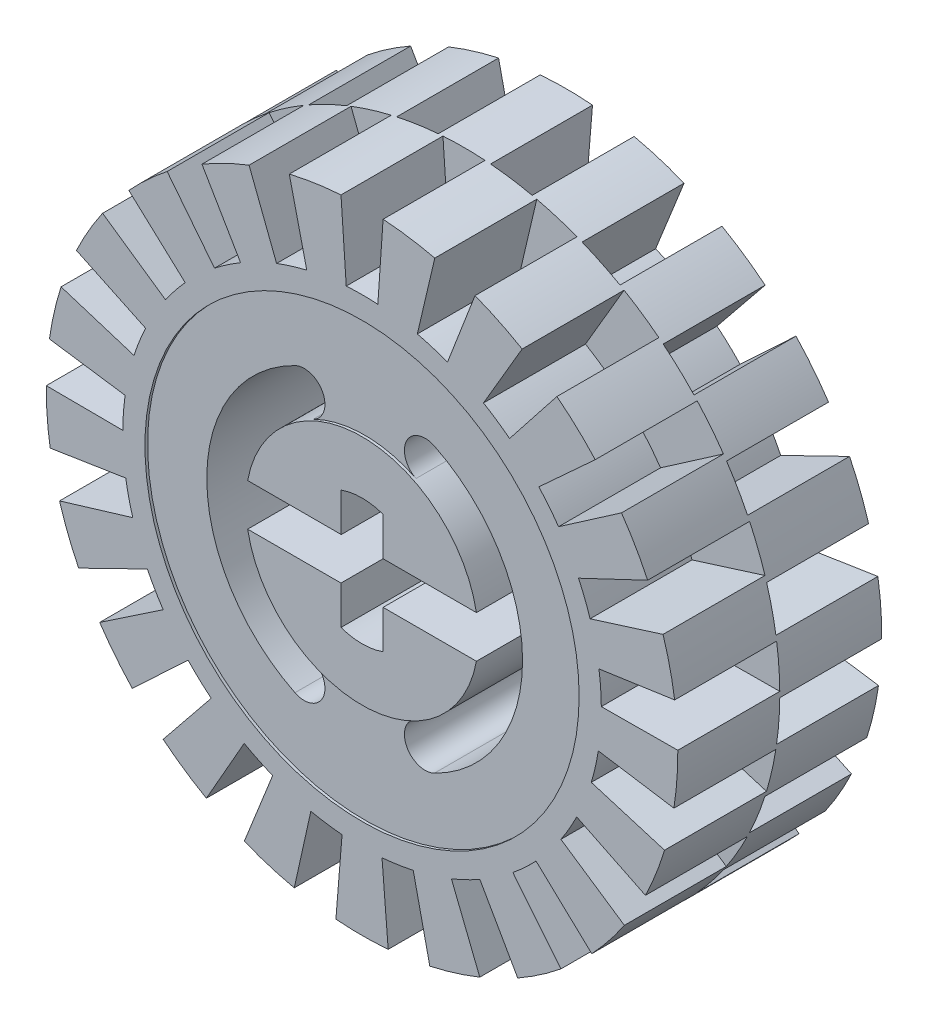
SolidWorks part; units mm, degrees
ref_plane "Plan de face" through (0, 0, 0) normal (0, 0, 1) x (1, 0, 0)
ref_plane "Plan de dessus" through (0, 0, 0) normal (0, 1, 0) x (1, 0, 0)
ref_plane "Plan de droite" through (0, 0, 0) normal (1, 0, 0) x (0, 0, -1)
sketch "Esquisse1" plane through (0, 0, 0) normal (0, 0, 1) x (1, 0, 0)
  circle A0 centre (0, 0) radius 12
  dimension "D1" = 24
extrude "Boss.-Extru.1" add sketch "Esquisse1" along normal blind 7.75
sketch "Esquisse2" plane through (0, 0, 7.75) normal (0, 0, 1) x (1, 0, 0)
  line L0 (-0.8, 11.9733) -> (-0.6, 9.0733) construction
  line L1 (-0.6, 9.0733) -> (0.6, 9.0733) construction
  line L2 (0.8, 11.9733) -> (0.6, 9.0733) construction
  line L3 (-0.8, 11.9733) -> (-0.6, 9.0733)
  line L4 (-0.8, 11.9733) -> (0.8, 11.9733) construction
  line L5 (0, 11.9733) -> (0, 0) construction
  line L6 (0.6, 9.0733) -> (0.8, 11.9733)
  line L7 (-0.8, 11.9733) -> (-1.2164, 18.0106)
  line L8 (-1.2164, 18.0106) -> (1.2164, 18.0106)
  line L9 (1.2164, 18.0106) -> (0.8, 11.9733)
  line L10 (2.7647, 11.6772) -> (2.1011, 8.8471)
  line L11 (2.7647, 11.6772) -> (4.1464, 17.5689)
  line L12 (4.1464, 17.5689) -> (6.471, 16.8519)
  line L13 (6.471, 16.8519) -> (4.2937, 11.2056)
  line L14 (3.2477, 8.4933) -> (4.2937, 11.2056)
  line L15 (6.0838, 10.3435) -> (4.6154, 7.8347)
  line L16 (6.0838, 10.3435) -> (9.1407, 15.5662)
  line L17 (9.1407, 15.5662) -> (11.1507, 14.1958)
  line L18 (11.1507, 14.1958) -> (7.4058, 9.4422)
  line L19 (5.6069, 7.1587) -> (7.4058, 9.4422)
  line L20 (8.8623, 8.0907) -> (6.7197, 6.1262)
  line L21 (8.8623, 8.0907) -> (13.3228, 12.1804)
  line L22 (13.3228, 12.1804) -> (14.8396, 10.2784)
  line L23 (14.8396, 10.2784) -> (9.8599, 6.8398)
  line L24 (7.4679, 5.188) -> (9.8599, 6.8398)
  line L25 (10.8534, 5.119) -> (8.2269, 3.8734)
  line L26 (10.8534, 5.119) -> (16.3212, 7.7123)
  line L27 (16.3212, 7.7123) -> (17.21, 5.4477)
  line L28 (17.21, 5.4477) -> (11.4379, 3.6296)
  line L29 (8.6653, 2.7563) -> (11.4379, 3.6296)
  line L30 (11.88, 1.6925) -> (9.0031, 1.2764)
  line L31 (11.88, 1.6925) -> (17.8693, 2.5589)
  line L32 (17.8693, 2.5589) -> (18.0511, 0.133)
  line L33 (18.0511, 0.133) -> (11.9996, 0.097)
  line L34 (9.0928, 0.0797) -> (11.9996, 0.097)
  line L35 (11.8511, -1.8844) -> (8.9793, -1.434)
  line L36 (11.8511, -1.8844) -> (17.8297, -2.8219)
  line L37 (17.8297, -2.8219) -> (17.2883, -5.1936)
  line L38 (17.2883, -5.1936) -> (11.4951, -3.4443)
  line L39 (8.7123, -2.604) -> (11.4951, -3.4443)
  line L40 (10.7692, -5.2938) -> (8.1577, -4.017)
  line L41 (10.7692, -5.2938) -> (16.2058, -7.9519)
  line L42 (16.2058, -7.9519) -> (14.9894, -10.0587)
  line L43 (14.9894, -10.0587) -> (9.9692, -6.6795)
  line L44 (7.5577, -5.0563) -> (9.9692, -6.6795)
  line L45 (8.7304, -8.2329) -> (6.6112, -6.2431)
  line L46 (8.7304, -8.2329) -> (13.142, -12.3753)
  line L47 (13.142, -12.3753) -> (11.3586, -14.03)
  line L48 (11.3586, -14.03) -> (7.5575, -9.3212)
  line L49 (5.7316, -7.0593) -> (7.5575, -9.3212)
  line L50 (5.9158, -10.4405) -> (4.4773, -7.9144)
  line L51 (5.9158, -10.4405) -> (8.9104, -15.6992)
  line L52 (8.9104, -15.6992) -> (6.7186, -16.7547)
  line L53 (6.7186, -16.7547) -> (4.4742, -11.1347)
  line L54 (3.3962, -8.4351) -> (4.4742, -11.1347)
  line L55 (2.5756, -11.7203) -> (1.9456, -8.8825)
  line L56 (2.5756, -11.7203) -> (3.8871, -17.6281)
  line L57 (3.8871, -17.6281) -> (1.4816, -17.9907)
  line L58 (1.4816, -17.9907) -> (0.9935, -11.9588)
  line L59 (0.759, -9.0614) -> (0.9935, -11.9588)
  line L60 (-0.9935, -11.9588) -> (-0.759, -9.0614)
  line L61 (-0.9935, -11.9588) -> (-1.4816, -17.9907)
  line L62 (-1.4816, -17.9907) -> (-3.8871, -17.6281)
  line L63 (-3.8871, -17.6281) -> (-2.5756, -11.7203)
  line L64 (-1.9456, -8.8825) -> (-2.5756, -11.7203)
  line L65 (-4.4742, -11.1347) -> (-3.3962, -8.4351)
  line L66 (-4.4742, -11.1347) -> (-6.7186, -16.7547)
  line L67 (-6.7186, -16.7547) -> (-8.9104, -15.6992)
  line L68 (-8.9104, -15.6992) -> (-5.9158, -10.4405)
  line L69 (-4.4773, -7.9144) -> (-5.9158, -10.4405)
  line L70 (-7.5575, -9.3212) -> (-5.7316, -7.0593)
  line L71 (-7.5575, -9.3212) -> (-11.3586, -14.03)
  line L72 (-11.3586, -14.03) -> (-13.142, -12.3753)
  line L73 (-13.142, -12.3753) -> (-8.7304, -8.2329)
  line L74 (-6.6112, -6.2431) -> (-8.7304, -8.2329)
  line L75 (-9.9692, -6.6795) -> (-7.5577, -5.0563)
  line L76 (-9.9692, -6.6795) -> (-14.9894, -10.0587)
  line L77 (-14.9894, -10.0587) -> (-16.2058, -7.9519)
  line L78 (-16.2058, -7.9519) -> (-10.7692, -5.2938)
  line L79 (-8.1577, -4.017) -> (-10.7692, -5.2938)
  line L80 (-11.4951, -3.4443) -> (-8.7123, -2.604)
  line L81 (-11.4951, -3.4443) -> (-17.2883, -5.1936)
  line L82 (-17.2883, -5.1936) -> (-17.8297, -2.8219)
  line L83 (-17.8297, -2.8219) -> (-11.8511, -1.8844)
  line L84 (-8.9793, -1.434) -> (-11.8511, -1.8844)
  line L85 (-11.9996, 0.097) -> (-9.0928, 0.0797)
  line L86 (-11.9996, 0.097) -> (-18.0511, 0.133)
  line L87 (-18.0511, 0.133) -> (-17.8693, 2.5589)
  line L88 (-17.8693, 2.5589) -> (-11.88, 1.6925)
  line L89 (-9.0031, 1.2764) -> (-11.88, 1.6925)
  line L90 (-11.4379, 3.6296) -> (-8.6653, 2.7563)
  line L91 (-11.4379, 3.6296) -> (-17.21, 5.4477)
  line L92 (-17.21, 5.4477) -> (-16.3212, 7.7123)
  line L93 (-16.3212, 7.7123) -> (-10.8534, 5.119)
  line L94 (-8.2269, 3.8734) -> (-10.8534, 5.119)
  line L95 (-9.8599, 6.8398) -> (-7.4679, 5.188)
  line L96 (-9.8599, 6.8398) -> (-14.8396, 10.2784)
  line L97 (-14.8396, 10.2784) -> (-13.3228, 12.1804)
  line L98 (-13.3228, 12.1804) -> (-8.8623, 8.0907)
  line L99 (-6.7197, 6.1262) -> (-8.8623, 8.0907)
  line L100 (-7.4058, 9.4422) -> (-5.6069, 7.1587)
  line L101 (-7.4058, 9.4422) -> (-11.1507, 14.1958)
  line L102 (-11.1507, 14.1958) -> (-9.1407, 15.5662)
  line L103 (-9.1407, 15.5662) -> (-6.0838, 10.3435)
  line L104 (-4.6154, 7.8347) -> (-6.0838, 10.3435)
  line L105 (-4.2937, 11.2056) -> (-3.2477, 8.4933)
  line L106 (-4.2937, 11.2056) -> (-6.471, 16.8519)
  line L107 (-6.471, 16.8519) -> (-4.1464, 17.5689)
  line L108 (-4.1464, 17.5689) -> (-2.7647, 11.6772)
  line L109 (-2.1011, 8.8471) -> (-2.7647, 11.6772)
  circle A1 centre (0, 0) radius 12 construction
  arc A2 (0.6, 9.0733) -> (-0.6, 9.0733) centre (0, 0) ccw
  arc A3 (3.2477, 8.4933) -> (2.1011, 8.8471) centre (0, 0) ccw
  arc A4 (5.6069, 7.1587) -> (4.6154, 7.8347) centre (0, 0) ccw
  arc A5 (7.4679, 5.188) -> (6.7197, 6.1262) centre (0, 0) ccw
  arc A6 (8.6653, 2.7563) -> (8.2269, 3.8734) centre (0, 0) ccw
  arc A7 (9.0928, 0.0797) -> (9.0031, 1.2764) centre (0, 0) ccw
  arc A8 (8.7123, -2.604) -> (8.9793, -1.434) centre (0, 0) ccw
  arc A9 (7.5577, -5.0563) -> (8.1577, -4.017) centre (0, 0) ccw
  arc A10 (5.7316, -7.0593) -> (6.6112, -6.2431) centre (0, 0) ccw
  arc A11 (3.3962, -8.4351) -> (4.4773, -7.9144) centre (0, 0) ccw
  arc A12 (0.759, -9.0614) -> (1.9456, -8.8825) centre (0, 0) ccw
  arc A13 (-1.9456, -8.8825) -> (-0.759, -9.0614) centre (0, 0) ccw
  arc A14 (-4.4773, -7.9144) -> (-3.3962, -8.4351) centre (0, 0) ccw
  arc A15 (-6.6112, -6.2431) -> (-5.7316, -7.0593) centre (0, 0) ccw
  arc A16 (-8.1577, -4.017) -> (-7.5577, -5.0563) centre (0, 0) ccw
  arc A17 (-8.9793, -1.434) -> (-8.7123, -2.604) centre (0, 0) ccw
  arc A18 (-9.0031, 1.2764) -> (-9.0928, 0.0797) centre (0, 0) ccw
  arc A19 (-8.2269, 3.8734) -> (-8.6653, 2.7563) centre (0, 0) ccw
  arc A20 (-6.7197, 6.1262) -> (-7.4679, 5.188) centre (0, 0) ccw
  arc A21 (-4.6154, 7.8347) -> (-5.6069, 7.1587) centre (0, 0) ccw
  arc A22 (-2.1011, 8.8471) -> (-3.2477, 8.4933) centre (0, 0) ccw
  point P1 (0, 9.0733)
  point P134 (0, 0)
  dimension "D1" = 2.9
  dimension "D2" = 1.2
  dimension "D3" = 21
  dimension "D4" = 1.6
extrude "Enlèv. mat.-Extru.1" cut sketch "Esquisse2" against normal blind 3.875
sketch "Esquisse3" plane through (0, 0, 0) normal (0, 0, -1) x (-1, 0, 0)
  line L0 (0, 0) -> (2.0891, 13.9787) construction
  line L1 (0.9786, 11.96) -> (2.561, 11.7235) construction
  line L2 (1.1507, 14.119) -> (0.7474, 9.06)
  line L3 (1.1507, 14.119) -> (3.0276, 13.8385)
  line L4 (3.0276, 13.8385) -> (1.9342, 8.8827)
  line L5 (0, 0) -> (17.443, 0) construction
  line L6 (5.2612, 13.1526) -> (3.3847, 8.4372)
  line L7 (5.2612, 13.1526) -> (6.9721, 12.3313)
  line L8 (6.9721, 12.3313) -> (4.4665, 7.9179)
  line L9 (8.9042, 11.0175) -> (5.7212, 7.0647)
  line L10 (8.9042, 11.0175) -> (10.297, 9.7284)
  line L11 (10.297, 9.7284) -> (6.6019, 6.2496)
  line L12 (11.7561, 7.9034) -> (7.5494, 5.0645)
  line L13 (11.7561, 7.9034) -> (12.7071, 6.2611)
  line L14 (12.7071, 6.2611) -> (8.1507, 4.026)
  line L15 (13.5634, 4.0871) -> (8.7068, 2.6143)
  line L16 (13.5634, 4.0871) -> (13.988, 2.2374)
  line L17 (13.988, 2.2374) -> (8.9753, 1.4447)
  line L18 (14.1655, -0.0923) -> (9.0906, -0.0682)
  line L19 (14.1655, -0.0923) -> (14.0261, -1.985)
  line L20 (14.0261, -1.985) -> (9.0024, -1.265)
  line L21 (13.509, -4.2636) -> (8.6666, -2.7447)
  line L22 (13.509, -4.2636) -> (12.8178, -6.0311)
  line L23 (12.8178, -6.0311) -> (8.2296, -3.8623)
  line L24 (11.6521, -8.056) -> (7.4725, -5.1773)
  line L25 (11.6521, -8.056) -> (10.4707, -9.5412)
  line L26 (10.4707, -9.5412) -> (6.7255, -6.1164)
  line L27 (8.7599, -11.1326) -> (5.6145, -7.1498)
  line L28 (8.7599, -11.1326) -> (7.1932, -12.2036)
  line L29 (7.1932, -12.2036) -> (4.6239, -7.827)
  line L30 (5.0893, -13.22) -> (3.2576, -8.4871)
  line L31 (5.0893, -13.22) -> (3.2765, -13.7817)
  line L32 (3.2765, -13.7817) -> (2.1114, -8.8422)
  line L33 (0.9665, -14.1328) -> (0.6113, -9.0702)
  line L34 (0.9665, -14.1328) -> (-0.9313, -14.1352)
  line L35 (-0.9313, -14.1352) -> (-0.5887, -9.0717)
  line L36 (-3.2421, -13.7898) -> (-2.0893, -8.8475)
  line L37 (-3.2421, -13.7898) -> (-5.0563, -13.2327)
  line L38 (-5.0563, -13.2327) -> (-3.2365, -8.4952)
  line L39 (-7.1627, -12.2215) -> (-4.6044, -7.8385)
  line L40 (-7.1627, -12.2215) -> (-8.7321, -11.1544)
  line L41 (-8.7321, -11.1544) -> (-5.5967, -7.1638)
  line L42 (-10.4469, -9.5673) -> (-6.7102, -6.1331)
  line L43 (-10.4469, -9.5673) -> (-11.632, -8.085)
  line L44 (-11.632, -8.085) -> (-7.4596, -5.1959)
  line L45 (-12.8028, -6.063) -> (-8.2199, -3.8828)
  line L46 (-12.8028, -6.063) -> (-13.4983, -4.2973)
  line L47 (-13.4983, -4.2973) -> (-8.6597, -2.7663)
  line L48 (-14.0211, -2.02) -> (-8.9992, -1.2874)
  line L49 (-14.0211, -2.02) -> (-14.1652, -0.1277)
  line L50 (-14.1652, -0.1277) -> (-9.0904, -0.0909)
  line L51 (-13.9935, 2.2026) -> (-8.9789, 1.4223)
  line L52 (-13.9935, 2.2026) -> (-13.5735, 4.0533)
  line L53 (-13.5735, 4.0533) -> (-8.7133, 2.5926)
  line L54 (-12.7226, 6.2294) -> (-8.1607, 4.0057)
  line L55 (-12.7226, 6.2294) -> (-11.7758, 7.8741)
  line L56 (-11.7758, 7.8741) -> (-7.562, 5.0457)
  line L57 (-10.3213, 9.7027) -> (-6.6174, 6.2332)
  line L58 (-10.3213, 9.7027) -> (-8.9317, 10.9952)
  line L59 (-8.9317, 10.9952) -> (-5.7388, 7.0505)
  line L60 (-7.0028, 12.3139) -> (-4.4862, 7.9068)
  line L61 (-7.0028, 12.3139) -> (-5.294, 13.1394)
  line L62 (-5.294, 13.1394) -> (-3.4057, 8.4288)
  line L63 (-3.0621, 13.8309) -> (-1.9563, 8.8778)
  line L64 (-3.0621, 13.8309) -> (-1.1859, 14.1161)
  line L65 (-1.1859, 14.1161) -> (-0.77, 9.0581)
  arc A0 (1.9342, 8.8827) -> (0.7474, 9.06) centre (0, 0) ccw
  circle A1 centre (0, 0) radius 12 construction
  arc A2 (4.4665, 7.9179) -> (3.3847, 8.4372) centre (0, 0) ccw
  arc A3 (6.6019, 6.2496) -> (5.7212, 7.0647) centre (0, 0) ccw
  arc A4 (8.1507, 4.026) -> (7.5494, 5.0645) centre (0, 0) ccw
  arc A5 (8.9753, 1.4447) -> (8.7068, 2.6143) centre (0, 0) ccw
  arc A6 (9.0024, -1.265) -> (9.0906, -0.0682) centre (0, 0) ccw
  arc A7 (8.2296, -3.8623) -> (8.6666, -2.7447) centre (0, 0) ccw
  arc A8 (6.7255, -6.1164) -> (7.4725, -5.1773) centre (0, 0) ccw
  arc A9 (4.6239, -7.827) -> (5.6145, -7.1498) centre (0, 0) ccw
  arc A10 (2.1114, -8.8422) -> (3.2576, -8.4871) centre (0, 0) ccw
  arc A11 (-0.5887, -9.0717) -> (0.6113, -9.0702) centre (0, 0) ccw
  arc A12 (-3.2365, -8.4952) -> (-2.0893, -8.8475) centre (0, 0) ccw
  arc A13 (-5.5967, -7.1638) -> (-4.6044, -7.8385) centre (0, 0) ccw
  arc A14 (-7.4596, -5.1959) -> (-6.7102, -6.1331) centre (0, 0) ccw
  arc A15 (-8.6597, -2.7663) -> (-8.2199, -3.8828) centre (0, 0) ccw
  arc A16 (-9.0904, -0.0909) -> (-8.9992, -1.2874) centre (0, 0) ccw
  arc A17 (-8.7133, 2.5926) -> (-8.9789, 1.4223) centre (0, 0) ccw
  arc A18 (-7.562, 5.0457) -> (-8.1607, 4.0057) centre (0, 0) ccw
  arc A19 (-5.7388, 7.0505) -> (-6.6174, 6.2332) centre (0, 0) ccw
  arc A20 (-3.4057, 8.4288) -> (-4.4862, 7.9068) centre (0, 0) ccw
  arc A21 (-0.77, 9.0581) -> (-1.9563, 8.8778) centre (0, 0) ccw
  point P6 (1.7698, 11.8418)
  point P98 (0, 0)
  dimension "D1" = 1.6
  dimension "D2" = 0.6
  dimension "D3" = 2.9
  dimension "D4" = 81.5
  dimension "D5" = 21
extrude "Enlèv. mat.-Extru.2" cut sketch "Esquisse3" against normal blind 3.875
sketch "Esquisse4" plane through (0, 0, 0) normal (0, 0, -1) x (-1, 0, 0)
  line L0 (0, 8.4222) -> (0, -14.5777) construction
  line L1 (-4.347, 0.8) -> (-0.79, 0.8)
  line L2 (-0.79, 0.8) -> (-0.79, 2.2663)
  line L3 (0.79, 0.8) -> (0.79, 2.2663)
  line L4 (4.347, -0.8) -> (0.8, -0.8)
  line L5 (0.79, 0.8) -> (4.347, 0.8)
  line L6 (-0.8, -0.8) -> (-4.347, -0.8)
  line L7 (-0.8, -0.8) -> (-0.8, -2.2627)
  line L8 (0.8, -0.8) -> (0.8, -2.2627)
  arc A0 (2.6488, 5.3837) -> (1.9512, 3.966) centre (2.3, 4.6748) ccw
  arc A1 (2.6488, -5.3837) -> (2.6488, 5.3837) centre (0, 0) ccw
  arc A2 (1.9512, -3.966) -> (4.347, -0.8) centre (0, 0) ccw
  arc A3 (-4.347, -0.8) -> (-1.9512, -3.966) centre (0, 0) ccw
  arc A4 (-1.9512, 3.966) -> (-2.6488, 5.3837) centre (-2.3, 4.6748) ccw
  arc A5 (-2.6488, -5.3837) -> (-1.9512, -3.966) centre (-2.3, -4.6748) ccw
  arc A6 (1.9512, -3.966) -> (2.6488, -5.3837) centre (2.3, -4.6748) ccw
  arc A7 (-2.6488, 5.3837) -> (-2.6488, -5.3837) centre (0, 0) ccw
  arc A8 (-1.9512, 3.966) -> (-4.347, 0.8) centre (0, 0) ccw
  arc A9 (4.347, 0.8) -> (1.9512, 3.966) centre (0, 0) ccw
  arc A10 (-0.8, -2.2627) -> (0.8, -2.2627) centre (0, 0) ccw
  arc A11 (0.79, 2.2663) -> (-0.79, 2.2663) centre (0, 0) ccw
  dimension "D1" = 8.84
  dimension "D2" = 12
  dimension "D7" = 4.8
  dimension "D3" = 4.6
  dimension "D4" = 2.3
  dimension "D5" = 0.8
  dimension "D6" = 0.8
  dimension "D8" = 0.8
  dimension "D9" = 0.8
extrude "Enlèv. mat.-Extru.3" cut sketch "Esquisse4" against normal up to next
sketch "Esquisse5" plane through (0, 0, 0) normal (0, 0, -1) x (-1, 0, 0)
  circle A0 centre (0, 0) radius 8.25
  circle A2 centre (0, 0) radius 4.42
  dimension "D1" = 16.5
extrude "Enlèv. mat.-Extru.4" cut sketch "Esquisse5" against normal blind 0.1
sketch "Esquisse6" plane through (0, 0, 7.75) normal (0, 0, 1) x (1, 0, 0)
  circle A0 centre (0, 0) radius 8.25
  circle A1 centre (0, 0) radius 4.42
  dimension "D1" = 16.5
extrude "Enlèv. mat.-Extru.5" cut sketch "Esquisse6" against normal blind 0.1
